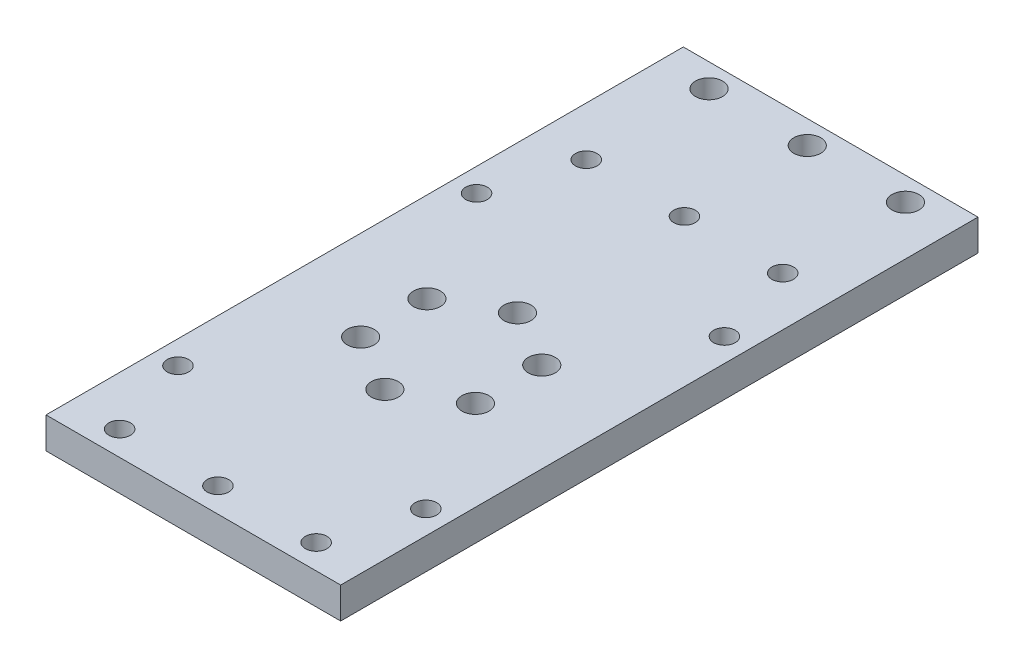
SolidWorks part; units mm, degrees
material "6061 Alloy"
ref_plane "Front Plane" through (0, 0, 0) normal (0, 0, 1) x (1, 0, 0)
ref_plane "Top Plane" through (0, 0, 0) normal (0, 1, 0) x (1, 0, 0)
ref_plane "Right Plane" through (0, 0, 0) normal (1, 0, 0) x (0, 0, -1)
sketch "Sketch1" plane through (0, 0, 0) normal (0, 1, 0) x (1, 0, 0)
  line L1 (-30, 80) -> (30, 80)
  line L2 (-30, 80) -> (-30, -80)
  line L3 (-30, -80) -> (30, -80)
  line L4 (30, 80) -> (30, -80)
  line L5 (0, -80) -> (0, 80) construction
  line L6 (-30, 0) -> (30, 0) construction
  point P0 (0, 0)
  dimension "D1" = 60
  dimension "D2" = 160
extrude "Boss-Extrude1" add sketch "Sketch1" along normal mid plane 6.35
sketch "Sketch3" plane through (0, 0, 0) normal (0, 1, 0) x (1, 0, 0)
  line L0 (0, 75.2375) -> (20, 75.2375) construction
  line L5 (0, -80) -> (0, 80) construction
  line L6 (-30, 0) -> (30, 0) construction
  line L7 (0, 50.2375) -> (20, 50.2375) construction
  line L8 (30, 80) -> (-30, 80) construction
  line L9 (-30, 80) -> (-30, -80) construction
  line L10 (-30, -80) -> (30, -80) construction
  line L11 (30, -80) -> (30, 80) construction
  line L12 (0, -44.7625) -> (20, -44.7625) construction
  circle A0 centre (20, 75.2375) radius 2.75
  circle A1 centre (20, 50.2375) radius 2.2
  circle A2 centre (-20, 50.2375) radius 2.2
  circle A3 centre (-20, 75.2375) radius 2.75
  circle A4 centre (0, 75.2375) radius 2.75
  circle A5 centre (0, 50.2375) radius 2.2
  circle A6 centre (20, -44.7625) radius 2.2
  circle A7 centre (-20, -44.7625) radius 2.2
  circle A8 centre (0, -44.7625) radius 2.2
  point P0 (0, 0)
  dimension "D4" = 5.5
  dimension "D5" = 4.4
  dimension "D1" = 4.7625
  dimension "D2" = 25
  dimension "D3" = 20
  dimension "D6" = 2
extrude "M4/5_through" cut sketch "Sketch3" against normal up to surface (3.175 mm away) and the other way blind 6.35 up to face at (0, -3.175, 0)
sketch "Sketch4" plane through (0, 0, -80) normal (0, 0, -1) x (-1, 0, 0)
  line L0 (0, 0) -> (-12, 0) construction
  line L1 (0, 0) -> (0, 3.175) construction
  line L2 (-30, 3.175) -> (30, 3.175) construction
  circle A0 centre (-12, 0) radius 1.3
  circle A1 centre (12, 0) radius 1.3
  dimension "D1" = 2.6
  dimension "D2" = 12
extrude "M3_DRILL" cut sketch "Sketch4" against normal blind 8
sketch "Sketch5" plane through (0, 3.175, 0) normal (0, 1, 0) x (1, 0, 0)
  line L0 (-20, -44.7625) -> (0, -44.7625) construction
  line L1 (-30, 80) -> (-30, -80) construction
  line L2 (0, 0) -> (0, -23.6676) construction
  line L3 (-20, 50.2375) -> (-20, -44.7625) construction
  line L4 (-20, 2.7375) -> (-9.1233, 2.7375) construction
  circle A0 centre (-25.2375, -27.6625) radius 2.2
  circle A1 centre (25.2375, -27.6625) radius 2.2
  circle A2 centre (25.2375, 33.1375) radius 2.2
  circle A3 centre (-25.2375, 33.1375) radius 2.2
  dimension "D2" = 4.4
  dimension "D1" = 17.1
  dimension "D3" = 4.7625
extrude "M4_through" cut sketch "Sketch5" against normal up to surface (6.35 mm away) up to face at (20, -3.175, -48.0375)
sketch "Sketch6" plane through (0, 3.175, 0) normal (0, 1, 0) x (1, 0, 0)
  line L0 (0, 2.7375) -> (0, 0) construction
  line L1 (-25.2375, 33.1375) -> (-25.2375, -27.6625) construction
  line L2 (0, 2.7375) -> (-25.2375, 2.7375) construction
  circle A0 centre (0, 2.7375) radius 13.5 construction
  circle A1 centre (0, 16.2375) radius 2.75
  circle A2 centre (11.6913, 9.4875) radius 2.75
  circle A3 centre (11.6913, -4.0125) radius 2.75
  circle A4 centre (0, -10.7625) radius 2.75
  circle A5 centre (-11.6913, -4.0125) radius 2.75
  circle A6 centre (-11.6913, 9.4875) radius 2.75
  point P18 (0, 2.7375)
  dimension "D1" = 27
  dimension "D2" = 5.5
  dimension "D3" = 6
extrude "M5_through" cut sketch "Sketch6" against normal up to surface (6.35 mm away) up to face at (-25.2375, -3.175, -30.9375)
sketch "Sketch7" plane through (0, 3.175, 0) normal (0, 1, 0) x (1, 0, 0)
  line L0 (-20, -44.7625) -> (20, -44.7625) construction
  line L1 (30, -80) -> (30, 80) construction
  line L2 (-30, -80) -> (30, -80)
  line L3 (-30, -80) -> (-30, -49.7625)
  line L4 (-30, -49.7625) -> (30, -49.7625)
  line L5 (30, -80) -> (30, -49.7625)
  line L6 (0, -49.7625) -> (0, -80) construction
  line L7 (-30, -64.8812) -> (30, -64.8812) construction
  point P324 (0, -64.8812)
  dimension "D1" = 5
extrude "Cut-Extrude1" cut sketch "Sketch7" against normal up to surface (6.35 mm away) up to face at (0, -3.175, -13.4875)
